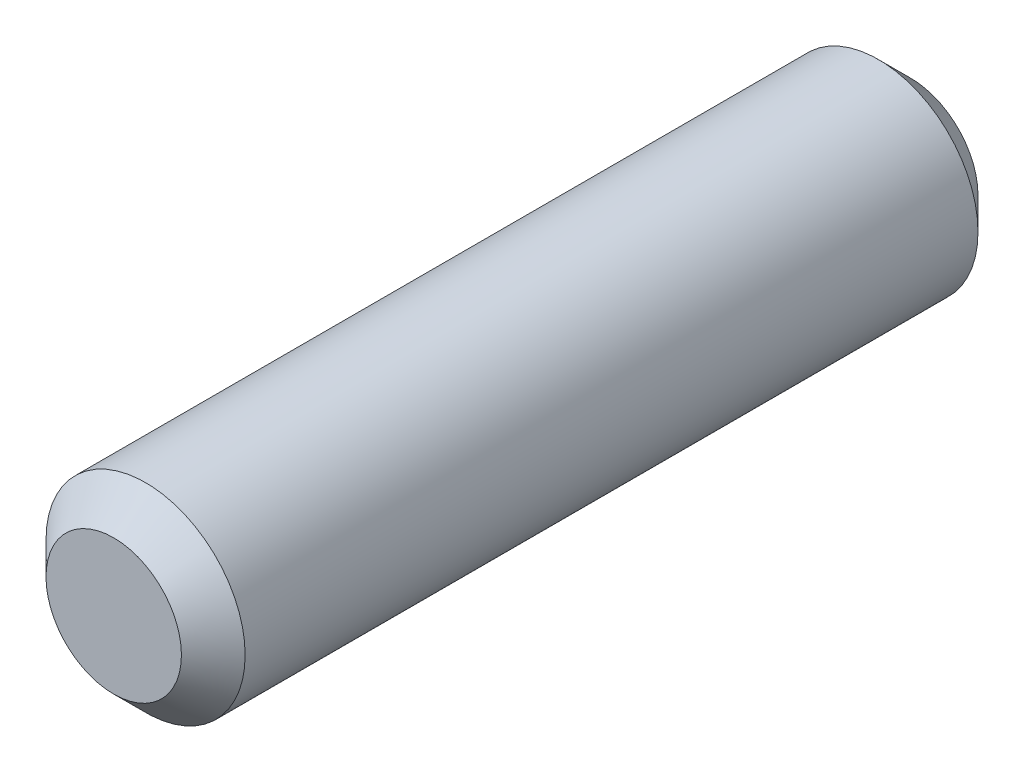
SolidWorks part; units mm, degrees
ref_plane "Front" through (0, 0, 0) normal (0, 0, 1) x (1, 0, 0)
ref_plane "Top" through (0, 0, 0) normal (0, 1, 0) x (1, 0, 0)
ref_plane "Right" through (0, 0, 0) normal (1, 0, 0) x (0, 0, -1)
sketch "Sketch1" plane through (0, 0, 0) normal (0, 0, 1) x (1, 0, 0)
  circle A0 centre (0, 0) radius 1.1906
  dimension "D1" = 2.3813
extrude "Boss-Extrude1" add sketch "Sketch1" along normal mid plane 9.525
chamfer "Chamfer1" distance 0.381 2 edges at (1.1906, 0, -4.7625) (1.1906, 0, 4.7625)
